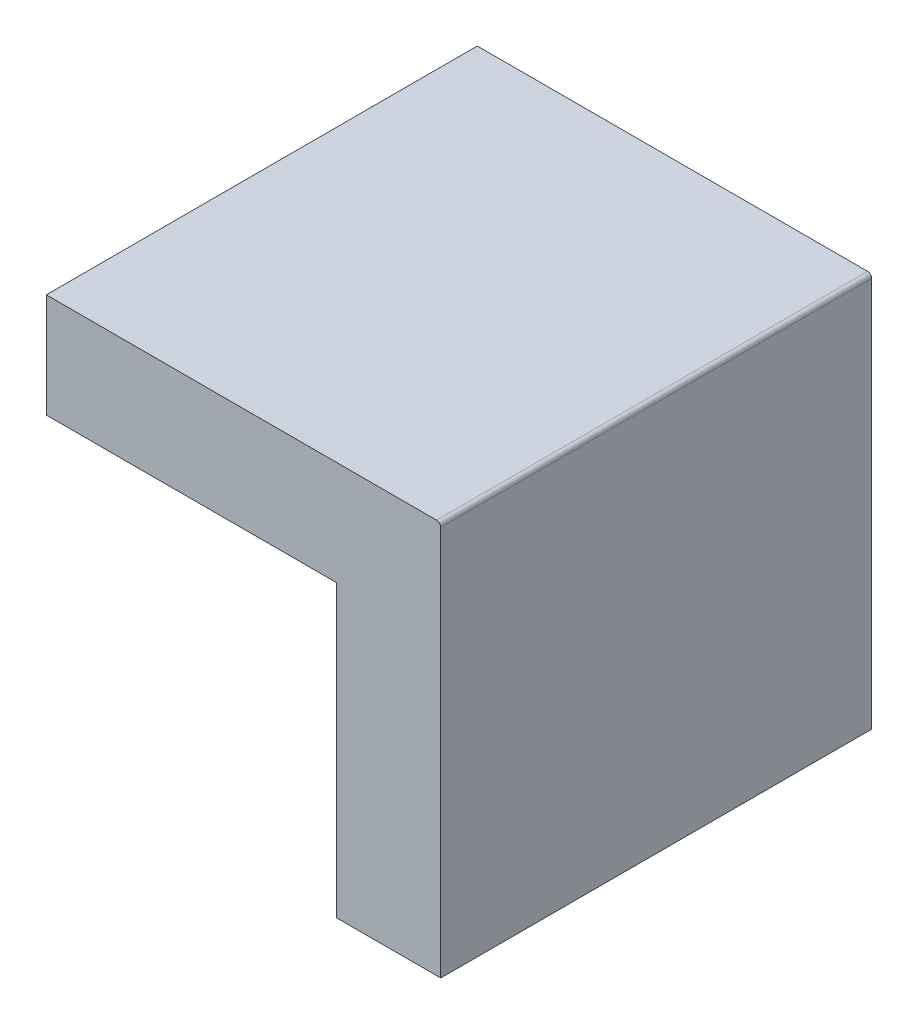
SolidWorks part; units mm, degrees
ref_plane "Front Plane" through (0, 0, 0) normal (0, 0, 1) x (1, 0, 0)
ref_plane "Top Plane" through (0, 0, 0) normal (0, 1, 0) x (1, 0, 0)
ref_plane "Right Plane" through (0, 0, 0) normal (1, 0, 0) x (0, 0, -1)
sketch "Sketch1" plane through (0, 0, 0) normal (0, 0, 1) x (1, 0, 0)
  line L0 (0, -200) -> (0, 0) construction
  line L1 (0, 0) -> (-100, 0) construction
  line L2 (-9.525, 0) -> (-923.925, 0)
  line L3 (0, -9.525) -> (0, -923.925)
  line L4 (-923.925, 0) -> (-923.925, -243.9381)
  line L5 (-923.925, -243.9381) -> (-243.9381, -243.9381)
  line L6 (-243.9381, -243.9381) -> (-243.9381, -923.925)
  line L7 (-243.9381, -923.925) -> (0, -923.925)
  arc A0 (0, -9.525) -> (-9.525, 0) centre (-9.525, -9.525) ccw
  dimension "D1" = 19.05
  dimension "D2" = 914.4
  dimension "D3" = 914.4
  dimension "D4" = 243.9381
extrude "Boss-Extrude2" add sketch "Sketch1" against normal offset from surface 304.8 and the other way offset from surface (304.8 mm away) 304.8 contours L3 A0 L2 L4 L5 L6 L7
